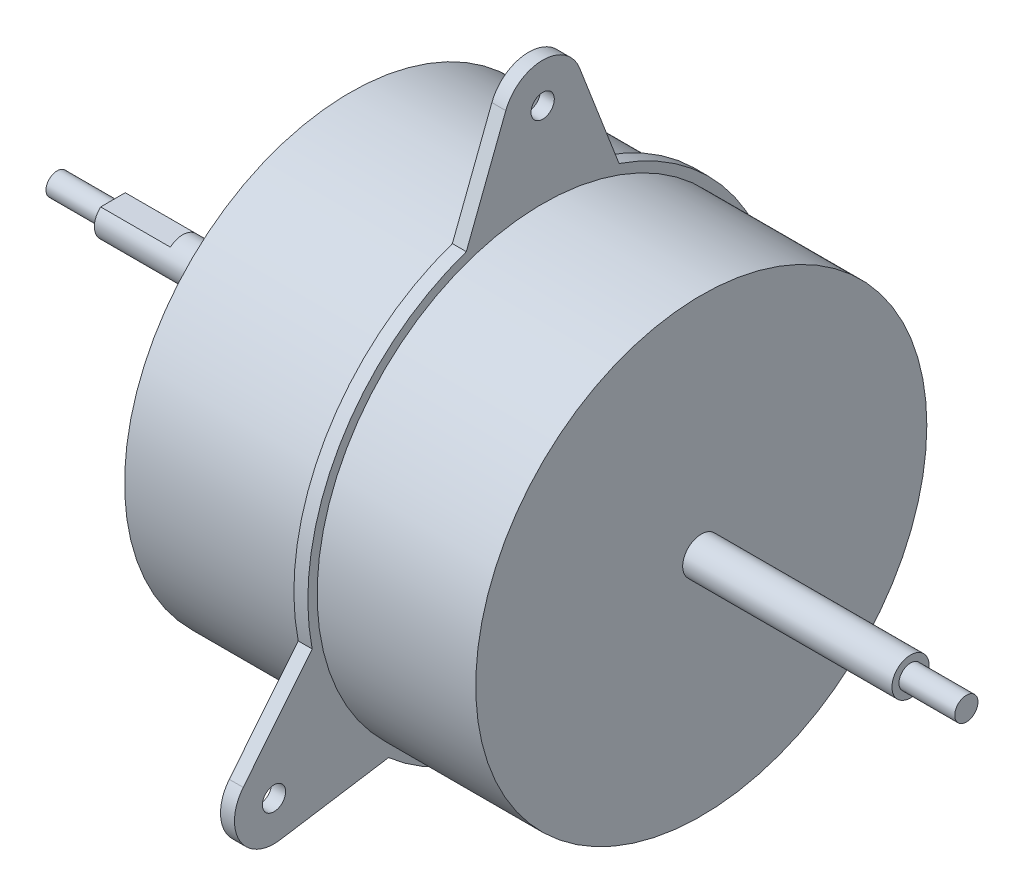
SolidWorks part; units mm, degrees
ref_plane "Front Plane" through (0, 0, 0) normal (0, 0, 1) x (1, 0, 0)
ref_plane "Top Plane" through (0, 0, 0) normal (0, 1, 0) x (1, 0, 0)
ref_plane "Right Plane" through (0, 0, 0) normal (1, 0, 0) x (0, 0, -1)
sketch "Sketch1" plane through (0, 0, 0) normal (0, 0, 1) x (1, 0, 0)
  line L0 (0, 0) -> (105.3598, 0) construction
  line L1 (0, 0) -> (-149.9442, 0) construction
  line L2 (0, 48.5) -> (37.1, 48.5)
  line L3 (37.1, 48.5) -> (37.1, 4)
  line L4 (37.1, 4) -> (82.1, 4)
  line L5 (82.1, 4) -> (82.1, 2.5)
  line L6 (82.1, 2.5) -> (94.1, 2.5)
  line L7 (94.1, 2.5) -> (94.1, 0)
  line L8 (0, 48.5) -> (-38.4, 48.5)
  line L9 (-38.4, 48.5) -> (-38.4, 4)
  line L10 (-38.4, 4) -> (-89.4, 4)
  line L11 (-89.4, 4) -> (-89.4, 2.4)
  line L12 (-89.4, 2.4) -> (-101.4, 2.4)
  line L13 (-101.4, 2.4) -> (-101.4, 0)
  line L14 (94.1, 0) -> (-101.4, 0)
  dimension "D1" = 97
  dimension "D2" = 38.4
  dimension "D3" = 75.5
  dimension "D4" = 8
  dimension "D5" = 5
  dimension "D6" = 12
  dimension "D7" = 57
  dimension "D8" = 63
  dimension "D9" = 12
  dimension "D10" = 4.8
revolve "Revolve1" add sketch "Sketch1" angle 360 about L1
sketch "Sketch2" plane through (0, 0, 0) normal (1, 0, 0) x (0, 0, -1)
  line L0 (-7.9306, 69.7715) -> (-16.4218, 47.7554)
  line L1 (0, 66.7128) -> (-57.775, -33.3564) construction
  line L2 (-57.775, -33.3564) -> (57.775, -33.3564) construction
  line L3 (57.775, -33.3564) -> (0, 66.7128) construction
  line L4 (0, 66.7128) -> (0, 84.9608) construction
  line L5 (7.9306, 69.7715) -> (16.4218, 47.7554)
  line L6 (64.3892, -28.0176) -> (49.5683, -9.656)
  line L7 (56.4586, -41.7539) -> (33.1465, -38.0994)
  line L8 (-56.4586, -41.7539) -> (-33.1465, -38.0994)
  line L9 (-64.3892, -28.0176) -> (-49.5683, -9.656)
  circle A0 centre (0, 0) radius 33.3564 construction
  circle A1 centre (0, 66.7128) radius 2.5
  circle A2 centre (57.775, -33.3564) radius 2.5
  circle A3 centre (-57.775, -33.3564) radius 2.5
  arc A4 (7.9306, 69.7715) -> (-7.9306, 69.7715) centre (0, 66.7128) ccw
  arc A5 (-53.525, -25.9952) -> (-56.4586, -41.7539) centre (-57.775, -33.3564) ccw construction
  arc A6 (56.4586, -41.7539) -> (64.3892, -28.0176) centre (57.775, -33.3564) ccw
  circle A7 centre (0, 66.7128) radius 8.5 construction
  circle A8 centre (57.775, -33.3564) radius 8.5 construction
  circle A9 centre (0, 0) radius 50.5
  arc A10 (-16.4218, 47.7554) -> (-49.5683, -9.656) centre (0, 0) ccw
  arc A11 (49.5683, -9.656) -> (16.4218, 47.7554) centre (0, 0) ccw
  circle A12 centre (-57.775, -33.3564) radius 8.5 construction
  arc A13 (-33.1465, -38.0994) -> (33.1465, -38.0994) centre (0, 0) ccw
  arc A14 (-64.3892, -28.0176) -> (-56.4586, -41.7539) centre (-57.775, -33.3564) ccw
  dimension "D1" = 5
  dimension "D2" = 115.55
  dimension "D3" = 6
  dimension "D4" = 2
  dimension "D5" = 3
extrude "Boss-Extrude1" add sketch "Sketch2" along normal blind 3
sketch "Sketch4" plane through (-89.4, 0, 0) normal (-1, 0, 0) x (0, 0, 1)
  line L0 (-2.6458, 3) -> (2.6458, 3)
  circle A0 centre (0, 0) radius 4 construction
  arc A1 (-2.6458, 3) -> (2.6458, 3) centre (0, 0) ccw construction
  arc A2 (-2.6458, 3) -> (2.6458, 3) centre (0, 0) cw
  point P7 (0, -4)
  dimension "D1" = 7
extrude "Cut-Extrude1" cut sketch "Sketch4" against normal blind 15
